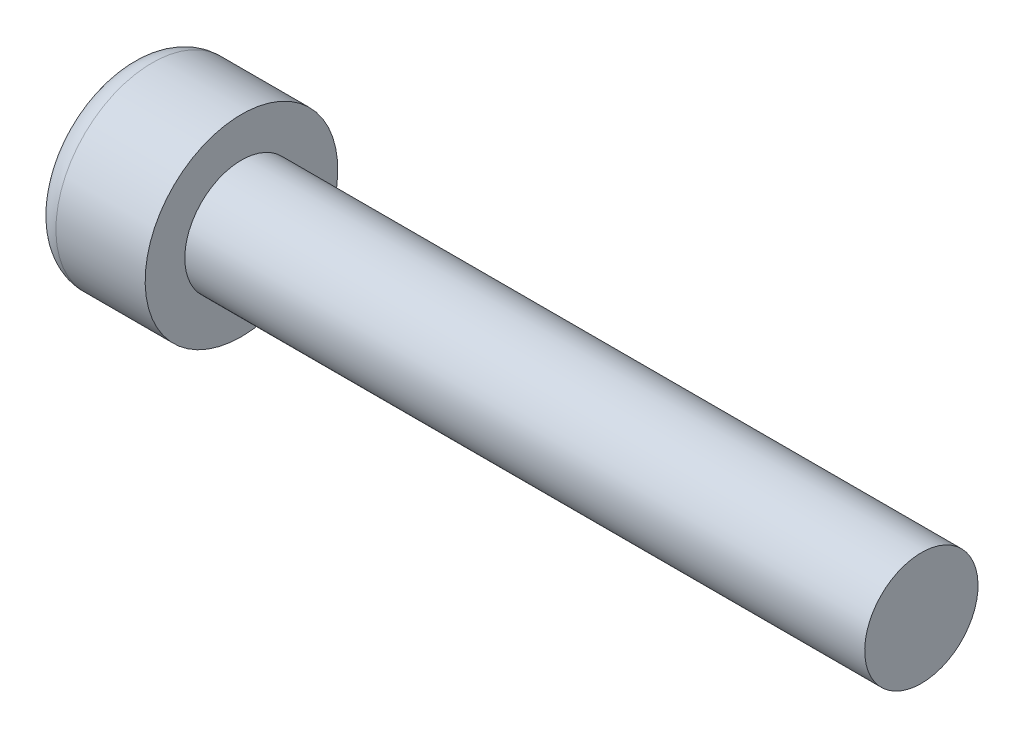
SolidWorks part; units mm, degrees
material "Plain Carbon Steel"
ref_plane "Front Plane" through (0, 0, 0) normal (0, 0, 1) x (1, 0, 0)
ref_plane "Top Plane" through (0, 0, 0) normal (0, 1, 0) x (1, 0, 0)
ref_plane "Right Plane" through (0, 0, 0) normal (1, 0, 0) x (0, 0, -1)
sketch "Sketch1" plane through (0, 0, 0) normal (0, 0, 1) x (1, 0, 0)
  line L0 (0, 0) -> (0, 3.1875)
  line L1 (1.0625, 4.25) -> (5, 4.25)
  line L2 (5, 4.25) -> (5, 2.5)
  line L3 (5, 2.5) -> (35, 2.5)
  line L4 (35, 2.5) -> (35, 0)
  line L5 (35, 0) -> (0, 0) construction
  line L6 (1.0625, 3.1875) -> (1.0625, 2.125) construction
  line L7 (1.0625, 2.125) -> (1.0625, 1.0625) construction
  line L8 (1.0625, 1.0625) -> (1.0625, 0) construction
  line L9 (1.0625, 4.25) -> (1.0625, 3.1875) construction
  line L10 (0, 0) -> (35, 0)
  arc A0 (0, 3.1875) -> (1.0625, 4.25) centre (1.0625, 3.1875) cw
  dimension "D1" = 5
  dimension "D2" = 8.5
  dimension "D3" = 5
  dimension "D4" = 30
revolve "Revolve1" add sketch "Sketch1" angle 360 about L10
sketch "Sketch2" plane through (0, 0, 0) normal (-1, 0, 0) x (0, 0, 1)
  line L1 (0, 2.3094) -> (-2, 1.1547)
  line L2 (-2, 1.1547) -> (-2, -1.1547)
  line L3 (-2, -1.1547) -> (0, -2.3094)
  line L4 (0, -2.3094) -> (2, -1.1547)
  line L5 (2, -1.1547) -> (2, 1.1547)
  line L6 (2, 1.1547) -> (0, 2.3094)
  circle A0 centre (0, 0) radius 2 construction
  dimension "D1" = 4
extrude "Cut-Extrude1" cut sketch "Sketch2" against normal blind 2.5
